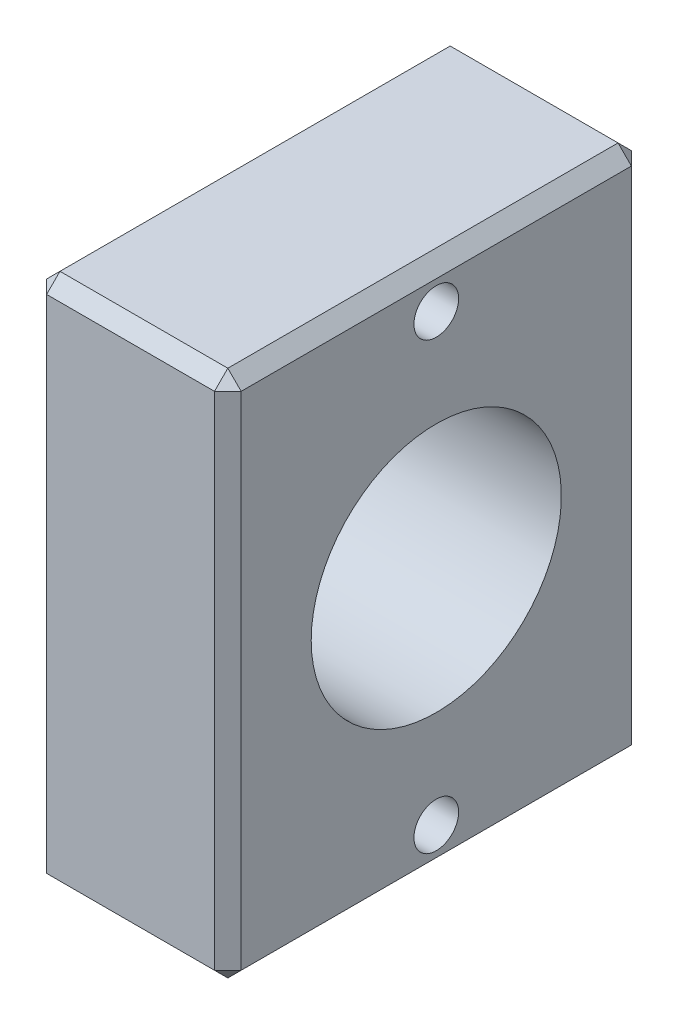
SolidWorks part; units mm, degrees
material "PET"
ref_plane "Front" through (0, 0, 0) normal (0, 0, 1) x (1, 0, 0)
ref_plane "Top" through (0, 0, 0) normal (0, 1, 0) x (1, 0, 0)
ref_plane "Right" through (0, 0, 0) normal (1, 0, 0) x (0, 0, -1)
sketch "Sketch1" plane through (0, 0, 0) normal (0, 1, 0) x (1, 0, 0)
  line L1 (11.1125, -23.8125) -> (-11.1125, -23.8125)
  line L2 (11.1125, -23.8125) -> (11.1125, 23.8125)
  line L3 (11.1125, 23.8125) -> (-11.1125, 23.8125)
  line L4 (-11.1125, -23.8125) -> (-11.1125, 23.8125)
  line L5 (11.1125, -23.8125) -> (-11.1125, 23.8125) construction
  line L6 (11.1125, 23.8125) -> (-11.1125, -23.8125) construction
  point P0 (0, 0)
  dimension "D1" = 22.225
  dimension "D2" = 47.625
extrude "Boss-Extrude1" add sketch "Sketch1" along normal mid plane 60.325
sketch "Sketch2" plane through (-11.1125, 0, 0) normal (-1, 0, 0) x (0, 0, 1)
  circle A0 centre (0, 0) radius 14.2875
  circle A1 centre (0, 25.4) radius 2.5527
  circle A2 centre (0, -25.4) radius 2.5527
  circle A3 centre (0, 0) radius 25.4 construction
  dimension "D1" = 28.575
  dimension "D2" = 50.8
  dimension "D3" = 5.1054
extrude "Cut-Extrude1" cut sketch "Sketch2" against normal through all
chamfer "Chamfer1" distance 1.524 angle 45 12 edges at (11.1125, -30.1625, 0) (-11.1125, -30.1625, 0) (11.1125, 0, -23.8125) (0, -30.1625, -23.8125) (-11.1125, 0, -23.8125) (0, 30.1625, -23.8125) (11.1125, 30.1625, 0) (-11.1125, 30.1625, 0) (-11.1125, 0, 23.8125) (0, 30.1625, 23.8125) (11.1125, 0, 23.8125) (0, -30.1625, 23.8125)
